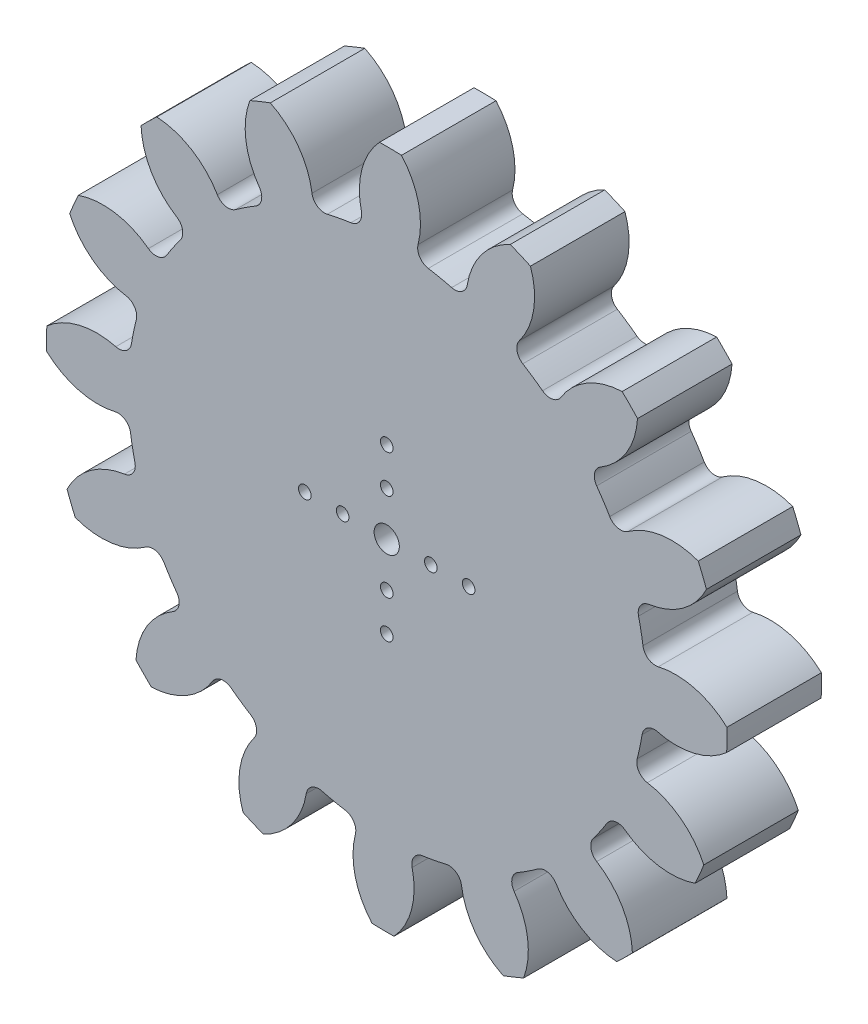
SolidWorks part; units mm, degrees
ref_plane "Front Plane" through (0, 0, 0) normal (0, 0, 1) x (1, 0, 0)
ref_plane "Top Plane" through (0, 0, 0) normal (0, 1, 0) x (1, 0, 0)
ref_plane "Right Plane" through (0, 0, 0) normal (1, 0, 0) x (0, 0, -1)
sketch "Basic Circles" plane through (0, 0, 0) normal (0, 0, 1) x (1, 0, 0)
  line L0 (0, 0) -> (0, 50000) construction
  line L2 (0, 0) -> (-50000, 0) construction
  circle A0 centre (0, 0) radius 41.058
  circle A1 centre (0, 0) radius 48
  circle A2 centre (0, 0) radius 54
sketch "Q-Circles" plane through (0, 0, 0) normal (0, 0, 1) x (1, 0, 0)
  line L0 (0, 0) -> (30.8538, 36.7701)
  line L1 (200000, 0) -> (-250000, 0) construction
  line L2 (0, -200000) -> (0, 250000) construction
  circle A0 centre (0, 0) radius 48 construction
  arc A1 (30.8538, 36.7701) -> (0, 0) centre (15.4269, 18.3851) cw construction
  arc A2 (23.1404, 27.5776) -> (42.3872, 33.4563) centre (30.8538, 36.7701) ccw construction
  circle A3 centre (0, 0) radius 54 construction
  circle A4 centre (0, 0) radius 46.4758 construction
  point P3 (23.1404, 27.5776)
  point P4 (30.8538, 36.7701)
  point P13 (37.8261, 27.0035)
  dimension "D3" = 12
  dimension "D2" = 24
sketch "Pressure Angle Circle" plane through (0, 0, 0) normal (0, 0, 1) x (1, 0, 0)
  line L0 (0, 0) -> (-8.3351, 47.2708)
  line L1 (0, -200000) -> (0, 250000) construction
  line L2 (17.1753, 48.2477) -> (44.5323, 25.2925) construction
  line L3 (-2.3132, 55.9191) -> (64.0208, 17.6211) construction
  line L4 (0, 0) -> (24, 41.5692)
  line L5 (0, 0) -> (30.8538, 36.7701) construction
  circle A0 centre (0, 0) radius 47.2708 construction
  circle A1 centre (0, 0) radius 48 construction
  point P10 (30.8538, 36.7701)
  point P11 (30.8538, 36.7701)
  point P16 (30.8538, 36.7701)
  point P18 (23.6354, 40.9377)
  dimension "D3" = 10
sketch "Pitch points" plane through (0, 0, 0) normal (0, 0, 1) x (1, 0, 0)
  line L0 (0, 0) -> (23.0916, 42.0806) construction
  line L1 (0, 0) -> (14.4384, 45.777) construction
  circle A2 centre (0, 0) radius 48 construction
  circle A3 centre (0, 0) radius 48 construction
  point P1 (12.5058, 70.9056)
  point P4 (18.638, 69.5458)
  point P5 (24.6284, 67.6568)
  point P6 (30.4314, 65.2528)
  point P9 (36.0028, 62.3522)
  point P10 (23.0916, 42.0806)
  point P15 (14.4384, 45.777)
  point P16 (5.2304, 47.7142)
  point P21 (-4.1787, 47.8178)
  point P22 (-13.4272, 46.0837)
  point P23 (-22.1597, 42.5787)
  point P28 (-30.0406, 37.4374)
  point P29 (-36.7671, 30.8575)
  point P30 (-42.0806, 23.0916)
  point P31 (-45.777, 14.4384)
  dimension "D2" = 11.25
  dimension "D1" = 9.42
  dimension "D3" = 10
sketch "Q-Circles (Even No Points)" plane through (0, 0, 0) normal (0, 0, 1) x (1, 0, 0)
  line L0 (0, 0) -> (-37.2252, 27.8259) construction
  line L1 (0, 0) -> (-23.7431, 39.9533) construction
  circle A0 centre (0, 0) radius 46.4758 construction
  circle A1 centre (0, 0) radius 46.4758 construction
  circle A3 centre (0, 0) radius 41.058 construction
  circle A4 centre (0, 0) radius 54 construction
  arc A5 (-51.6295, 15.824) -> (-39.4483, 11.3839) centre (-42.0806, 23.0916) ccw
  arc A6 (-32.089, 25.6136) -> (-41.6438, 34.3772) centre (-30.0406, 37.4374) cw
  point P10 (-45.0401, 11.4623)
  point P13 (-37.2252, 27.8259)
  point P15 (-23.7431, 39.9533)
  point P20 (-6.6463, 45.9981)
  point P23 (11.4623, 45.0401)
  point P24 (27.8259, 37.2252)
  dimension "D1" = 12
  dimension "D2" = 12
  dimension "D3" = 22.5
  dimension "D4" = 5
sketch "Q-Circles (Odd No Points)" plane through (0, 0, 0) normal (0, 0, 1) x (1, 0, 0)
  line L0 (0, 0) -> (-26.9997, 37.8288) construction
  line L1 (0, 0) -> (-10.468, 45.2816) construction
  circle A0 centre (0, 0) radius 46.4758 construction
  circle A3 centre (0, 0) radius 46.4758 construction
  arc A5 (-35.4982, 20.6309) -> (-47.1279, 26.3622) centre (-45.777, 14.4384) ccw
  arc A6 (-24.901, 32.6451) -> (-33.4521, 42.3905) centre (-36.7671, 30.8575) ccw
  circle A7 centre (0, 0) radius 41.058 construction
  circle A8 centre (0, 0) radius 54 construction
  point P14 (-26.9997, 37.8288)
  point P17 (-10.468, 45.2816)
  point P21 (7.6573, 45.8407)
  point P22 (24.6169, 39.4209)
  point P23 (-39.4209, 24.6169)
  point P24 (37.8288, 26.9997)
  dimension "D1" = 12
  dimension "D2" = 12
  dimension "D3" = 22.5
  dimension "D4" = 5
sketch "Gear Profile" plane through (0, 0, 0) normal (0, 0, 1) x (1, 0, 0)
  arc A1 (-36.131, 19.5015) -> (-48.9465, 22.8087) centre (-45.0401, 11.4623) ccw
  arc A5 (-39.0697, 12.622) -> (-50.3195, 19.5947) centre (-39.4209, 24.6169) cw
  arc A6 (-25.9178, 31.8438) -> (-36.4922, 39.8035) centre (-37.2252, 27.8259) ccw
  arc A7 (-31.2655, 26.6126) -> (-38.9905, 37.3596) centre (-26.9997, 37.8288) cw
  circle A8 centre (0, 0) radius 41.058 construction
  circle A9 centre (0, 0) radius 54 construction
sketch "Sketch12" plane through (0, 0, 0) normal (0, 0, 1) x (1, 0, 0)
  circle A0 centre (0, 0) radius 41.058 construction
  circle A1 centre (0, 0) radius 41.058
extrude "Boss-Extrude2" add sketch "Sketch12" along normal mid plane 15
sketch "Sketch13" plane through (0, 0, 0) normal (0, 0, 1) x (1, 0, 0)
  circle A4 centre (0, 0) radius 41.058 construction
  circle A5 centre (0, 0) radius 54 construction
  arc A6 (-36.131, 19.5015) -> (-48.9465, 22.8087) centre (-45.0401, 11.4623) ccw construction
  arc A7 (-50.3195, 19.5947) -> (-39.0697, 12.622) centre (-39.4209, 24.6169) ccw construction
  arc A8 (-36.131, 19.5015) -> (-39.0697, 12.622) centre (0, 0) ccw
  arc A9 (-48.9465, 22.8087) -> (-50.3195, 19.5947) centre (0, 0) ccw
  arc A10 (-36.131, 19.5015) -> (-48.9465, 22.8087) centre (-45.0401, 11.4623) ccw
  arc A11 (-50.3195, 19.5947) -> (-39.0697, 12.622) centre (-39.4209, 24.6169) ccw
extrude "Boss-Extrude3" add sketch "Sketch13" along normal mid plane 15
fillet "Fillet1" radius 2 2 edges at (-39.0697, 12.622, 0) (-36.131, 19.5015, 0)
pattern_circular "CirPattern2" count 16 over 360 about axis through (0, 0, 0) along (0, 0, 1) of "Boss-Extrude3", "Fillet1"
sketch "Croquis1" plane through (0, 0, -7.5) normal (0, 0, -1) x (-1, 0, 0)
  line L0 (0, 0) -> (7, 0) construction
  line L1 (0, 0) -> (-7, 0) construction
  line L2 (7, 0) -> (13, 0) construction
  line L3 (-7, 0) -> (-13, 0) construction
  circle A0 centre (0, 0) radius 18 construction
  circle A1 centre (7, 0) radius 1
  circle A2 centre (13, 0) radius 1
  circle A3 centre (-7, 0) radius 1
  circle A4 centre (-13, 0) radius 1
  dimension "D1" = 36
  dimension "D3" = 2
  dimension "D5" = 2
  dimension "D8" = 2
  dimension "D9" = 2
  dimension "D2" = 7
  dimension "D4" = 6
  dimension "D6" = 7
  dimension "D7" = 6
extrude "Cortar-Extruir1" cut sketch "Croquis1" against normal blind 15
sketch "Croquis2" plane through (0, 0, -7.5) normal (0, 0, -1) x (-1, 0, 0)
  circle A0 centre (0, 0) radius 2
  dimension "D1" = 4
extrude "Cortar-Extruir2" cut sketch "Croquis2" against normal blind 15
sketch "Sketch14" plane through (0, 0, -7.5) normal (0, 0, -1) x (-1, 0, 0)
  line L0 (0, 0) -> (0, 7) construction
  line L1 (0, 7) -> (0, 13) construction
  line L2 (0, 0) -> (0, -7) construction
  line L3 (0, -7) -> (0, -13) construction
  circle A0 centre (0, 7) radius 1
  circle A1 centre (0, 13) radius 1
  circle A2 centre (0, -7) radius 1
  circle A3 centre (0, -13) radius 1
  dimension "D2" = 2
  dimension "D4" = 2
  dimension "D7" = 2
  dimension "D8" = 2
  dimension "D1" = 7
  dimension "D3" = 6
  dimension "D5" = 7
  dimension "D6" = 6
extrude "Cut-Extrude1" cut sketch "Sketch14" against normal blind 15
equation "\"module\"= 6"
equation "\"no of teeth\" = 16"
equation "\"addendum\"= \"module\" * 1"
equation "\"clearence\"= \"module\" * .157"
equation "\"dedendum\"= \"addendum\" + \"clearence\""
equation "\"circular pitch\"= \"module\" * 3.14"
equation "\"D1@Basic Circles\" = \"module\" * \"no of teeth\""
equation "\"D2@Basic Circles\"= \"D1@Basic Circles\" + 2 * \"addendum\""
equation "\"D3@Basic Circles\" = \"D1@Basic Circles\" - 2 * \"dedendum\""
equation "\"D3@Q-Circles\"= \"module\" * \"no of teeth\" / 8"
equation "\"D1@Boss-Extrude2\"=\"module\"*2.5"
equation "\"D1@Boss-Extrude3\"=\"module\"*2.5"
equation "\"D1@Pitch points\"   = \"circular pitch\" / 2"
equation "\"D2@Pitch points\"   = ( \"D1@Pitch points\" * 360 ) / ( 3.14 * \"module\" * \"no of teeth\" )"
equation "\"D1@Q-Circles (Even No Points)\"= \"module\" * \"no of teeth\" / 8"
equation "\"D2@Q-Circles (Even No Points)\" = \"module\" * \"no of teeth\" / 8"
equation "\"D3@Q-Circles (Even No Points)\" = ( \"circular pitch\" / 2 * 360 ) / ( \"module\" * \"no of teeth\" * 3.14 ) * 2"
equation "\"D1@Q-Circles (Odd No Points)\"   = \"module\" * \"no of teeth\" / 8"
equation "\"D2@Q-Circles (Odd No Points)\"   = \"module\" * \"no of teeth\" / 8"
equation "\"D3@Q-Circles (Odd No Points)\" = ( \"circular pitch\" / 2 * 360 ) / ( \"module\" * \"no of teeth\" * 3.14 ) * 2"
equation "\"D1@CirPattern2\" = \"no of teeth\""
equation "\"Pressure Angle\"= 10deg"
equation "\"D2@Pressure Angle Circle\" = \"Pressure Angle\""
equation "\"D3@Pressure Angle Circle\" = \"Pressure Angle\""
equation "\"D1@Pressure Angle Circle\" = \"Pressure Angle\""
